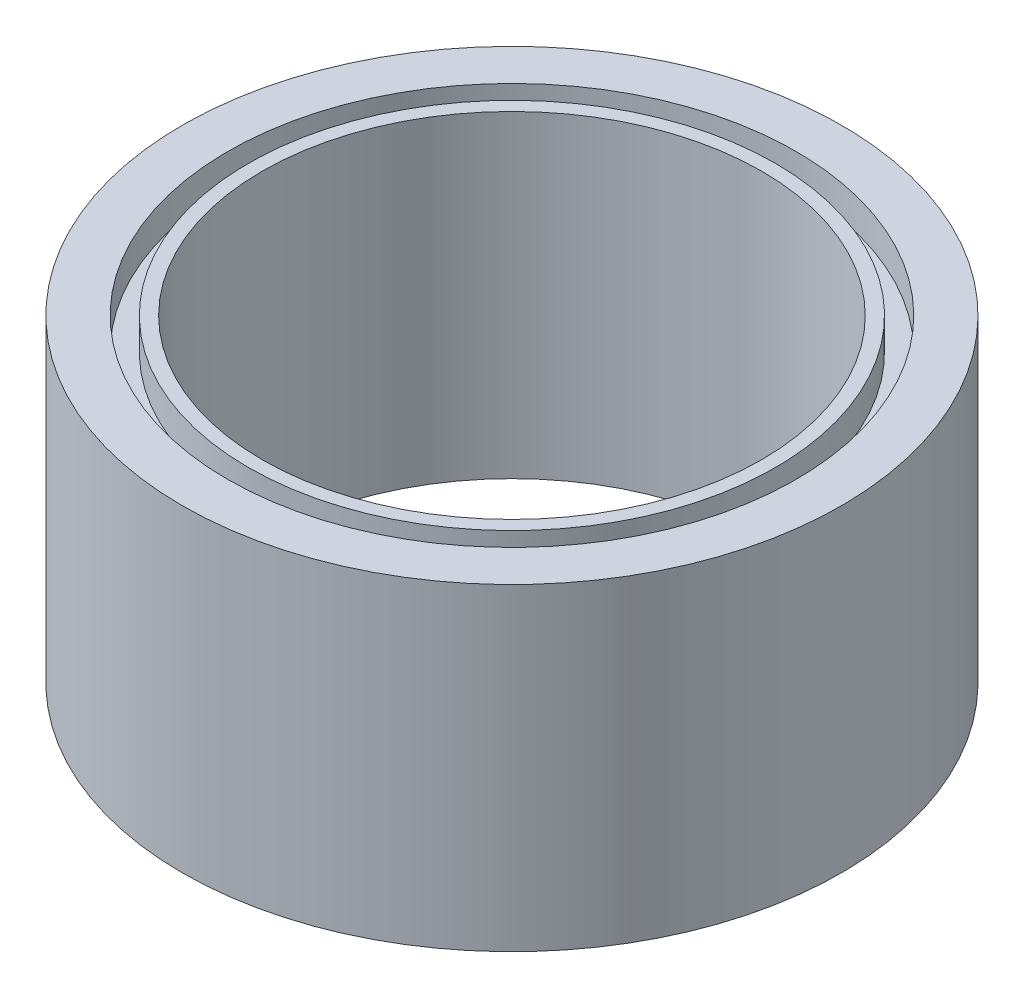
SolidWorks part; units mm, degrees
ref_plane "前基準面" through (0, 0, 0) normal (0, 0, 1) x (1, 0, 0)
ref_plane "上基準面" through (0, 0, 0) normal (0, 1, 0) x (1, 0, 0)
ref_plane "右基準面" through (0, 0, 0) normal (1, 0, 0) x (0, 0, -1)
sketch "草圖4" plane through (0, 0, 0) normal (0, 1, 0) x (1, 0, 0)
  circle A0 centre (0, 0) radius 72.55
extrude "上圓" add sketch "草圖4" along normal blind 70
sketch "草圖8" plane through (0, 70, 0) normal (0, 1, 0) x (1, 0, 0)
  circle A0 centre (0, 0) radius 62.55
  circle A1 centre (0, 0) radius 58
extrude "上圓溝槽" cut sketch "草圖8" against normal blind 7
sketch "草圖9" plane through (0, 70, 0) normal (0, 1, 0) x (1, 0, 0)
  circle A0 centre (0, 0) radius 55
extrude "除料-伸長3" cut sketch "草圖9" against normal blind 70
